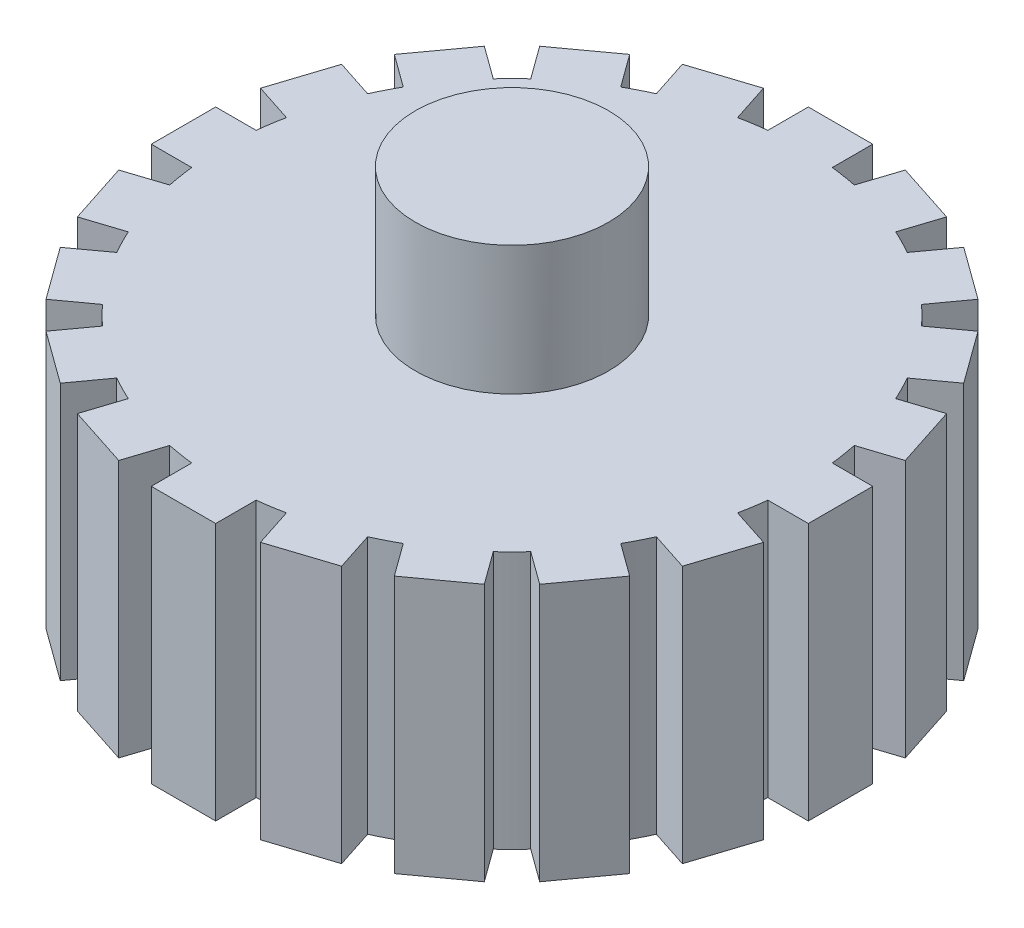
SolidWorks part; units mm, degrees
ref_plane "Plan de face" through (0, 0, 0) normal (0, 0, 1) x (1, 0, 0)
ref_plane "Plan de dessus" through (0, 0, 0) normal (0, 1, 0) x (1, 0, 0)
ref_plane "Plan de droite" through (0, 0, 0) normal (1, 0, 0) x (0, 0, -1)
sketch "Esquisse1" plane through (0, 0, 0) normal (0, 1, 0) x (1, 0, 0)
  circle A0 centre (0, 0) radius 7.5
  dimension "D1" = 15
extrude "Boss.-Extru.1" add sketch "Esquisse1" along normal blind 40
ref_plane "Plan1" through (0, 10, 0) normal (0, -1, 0) x (-1, 0, 0)
sketch "Esquisse2" plane through (0, 10, 0) normal (0, -1, 0) x (-1, 0, 0)
  circle A0 centre (0, 0) radius 22.5
  dimension "D1" = 45
extrude "Boss.-Extru.2" add sketch "Esquisse2" against normal blind 20
ref_plane "Plan2" through (0, 0, 22.5) normal (0, 0, 1) x (1, 0, 0)
sketch "Esquisse3" plane through (0, 0, 22.5) normal (0, 0, 1) x (1, 0, 0)
  line L0 (0, 10) -> (0, 30) construction
  line L1 (-8.25, 10) -> (8.25, 10) construction
  line L2 (22.5, 30) -> (-22.5, 30) construction
  line L4 (-2.5, 10) -> (2.5, 10)
  line L5 (-2.5, 10) -> (-2.5, 30)
  line L6 (-2.5, 30) -> (2.5, 30)
  line L7 (2.5, 10) -> (2.5, 30)
  line L8 (-2.5, 10) -> (2.5, 30) construction
  line L9 (-2.5, 30) -> (2.5, 10) construction
  point P6 (0, 20)
  dimension "D1" = 5
extrude "Boss.-Extru.3" add sketch "Esquisse3" along normal mid plane 6
pattern_circular "Répétition circulaire4" count 20 over 360 about axis through (0, 0, 0) along (0, 1, 0) of "Boss.-Extru.3"
